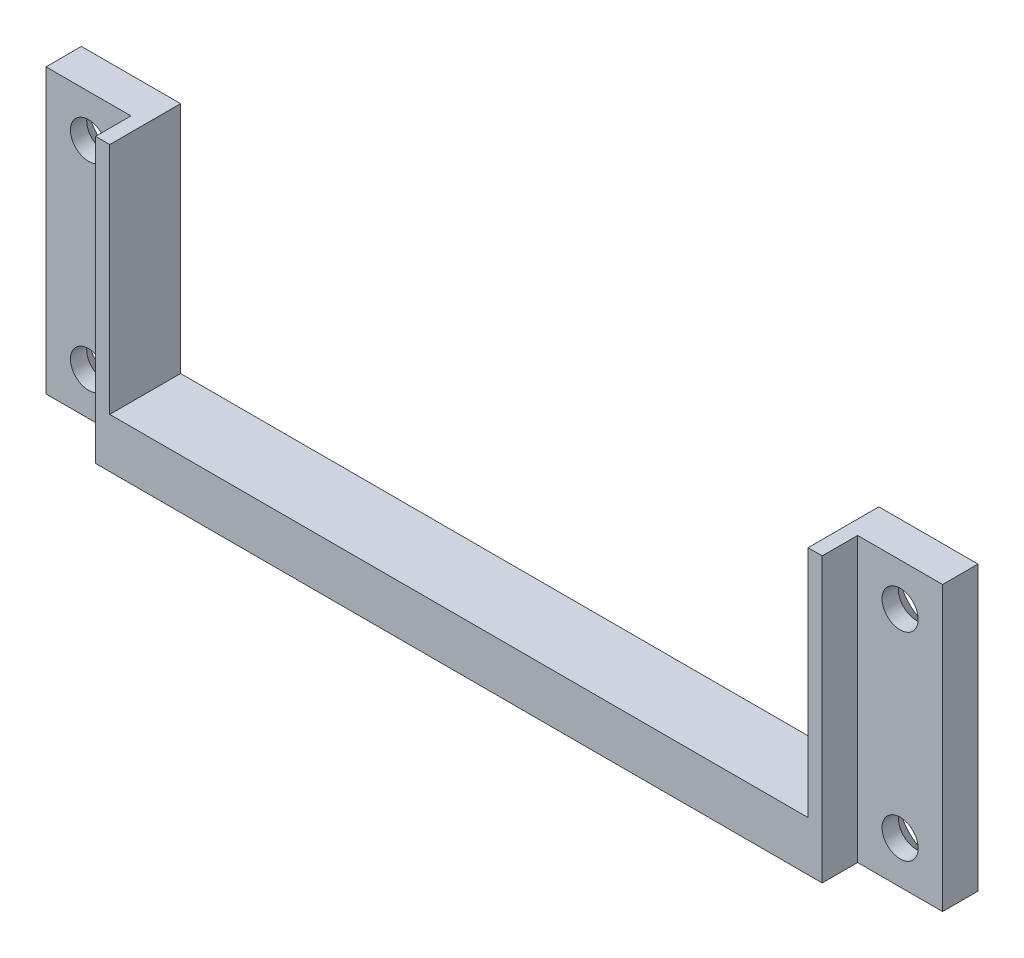
SolidWorks part; units mm, degrees
ref_plane "Plan de face" through (0, 0, 0) normal (0, 0, 1) x (1, 0, 0)
ref_plane "Plan de dessus" through (0, 0, 0) normal (0, 1, 0) x (1, 0, 0)
ref_plane "Plan de droite" through (0, 0, 0) normal (1, 0, 0) x (0, 0, -1)
sketch "Esquisse1" plane through (0, 0, 0) normal (0, 0, 1) x (1, 0, 0)
  line L1 (-17.4678, 19.1867) -> (85.1322, 19.1867)
  line L2 (-17.4678, 19.1867) -> (-17.4678, -15.8133)
  line L3 (-17.4678, -15.8133) -> (85.1322, -15.8133)
  line L4 (85.1322, 19.1867) -> (85.1322, -15.8133)
  dimension "D1" = 35
  dimension "D2" = 102.6
extrude "Boss.-Extru.1" add sketch "Esquisse1" along normal blind 10 and the other way blind 0.0001
sketch "Esquisse4" plane through (0, 19.1867, 0) normal (0, 1, 0) x (1, 0, 0)
  line L1 (-15.4678, -51.5999) -> (83.1322, -51.5999)
  line L2 (-15.4678, -51.5999) -> (-15.4678, 0.0001)
  line L3 (-15.4678, 0.0001) -> (83.1322, 0.0001)
  line L4 (83.1322, -51.5999) -> (83.1322, 0.0001)
  line L5 (-17.4678, -10) -> (-17.4678, 0.0001) construction
  line L6 (85.1322, -10) -> (85.1322, 0.0001) construction
  line L7 (85.1322, 0.0001) -> (-17.4678, 0.0001) construction
  dimension "D1" = 51.6
  dimension "D2" = 98.6
  dimension "D3" = 0
  dimension "D4" = 2
  dimension "D5" = 2
extrude "Enlèv. mat.-Extru.2" cut sketch "Esquisse4" against normal blind 33
sketch "Esquisse19" plane through (0, -15.8133, 0) normal (0, -1, 0) x (1, 0, 0)
  line L1 (85.1322, -0.0001) -> (-17.4678, -0.0001)
  line L2 (85.1322, -0.0001) -> (85.1322, 10)
  line L3 (85.1322, 10) -> (-17.4678, 10)
  line L4 (-17.4678, -0.0001) -> (-17.4678, 10)
extrude "Boss.-Extru.4" add sketch "Esquisse19" along normal blind 5
sketch "Esquisse21" plane through (-17.4678, 0, 0) normal (-1, 0, 0) x (0, 0, 1)
  line L0 (10, -20.8133) -> (-0.0001, -20.8133) construction
  line L1 (-0.0001, 19.1867) -> (4.9999, 19.1867)
  line L2 (-0.0001, 19.1867) -> (-0.0001, -20.8133)
  line L3 (-0.0001, -20.8133) -> (4.9999, -20.8133)
  line L4 (4.9999, 19.1867) -> (4.9999, -20.8133)
  dimension "D1" = 5
extrude "Boss.-Extru.5" add sketch "Esquisse21" along normal blind 12
sketch "Esquisse22" plane through (85.1322, 0, 0) normal (1, 0, 0) x (0, 0, -1)
  line L0 (0.0001, -20.8133) -> (-10, -20.8133) construction
  line L1 (0.0001, 19.1867) -> (-4.9999, 19.1867)
  line L2 (0.0001, 19.1867) -> (0.0001, -20.8133)
  line L3 (0.0001, -20.8133) -> (-4.9999, -20.8133)
  line L4 (-4.9999, 19.1867) -> (-4.9999, -20.8133)
  dimension "D1" = 5
extrude "Boss.-Extru.6" add sketch "Esquisse22" along normal blind 12
sketch "Esquisse23" plane through (0, 0, -0.0001) normal (0, 0, -1) x (-1, 0, 0)
  line L0 (-97.1322, -20.8133) -> (-97.1322, 19.1867) construction
  line L2 (-97.1322, 19.1867) -> (-83.1322, 19.1867) construction
  line L3 (29.4678, -20.8133) -> (-97.1322, -20.8133) construction
  line L4 (29.4678, 19.1867) -> (29.4678, -20.8133) construction
  line L5 (15.4678, 19.1867) -> (29.4678, 19.1867) construction
  circle A0 centre (-91.1322, 13.1867) radius 5.25
  circle A1 centre (-91.1322, -14.8133) radius 5.25
  circle A2 centre (23.4678, 13.1867) radius 5.25
  circle A3 centre (23.4678, -14.8133) radius 5.25
  dimension "D3" = 10.5
  dimension "D10" = 10.5
  dimension "D11" = 10.5
  dimension "D12" = 10.5
  dimension "D1" = 6
  dimension "D2" = 6
  dimension "D4" = 6
  dimension "D5" = 6
  dimension "D6" = 6
  dimension "D7" = 6
  dimension "D8" = 6
  dimension "D9" = 6
hole_wizard "Fraisage pour vis à tête fraisée bombée #51" positions "Esquisse3D1" profile "Esquisse24" countersink size "#5" standard "Ansi Inch" end condition through all
sketch3d "Esquisse3D1"
  point P0 (91.1322, 13.1867, -0.0001)
  point P3 (91.1322, -14.8133, -0.0001)
  point P6 (-23.4678, 13.1867, -0.0001)
  point P9 (-23.4678, -14.8133, -0.0001)
sketch "Esquisse24" plane through (91.1322, 13.1867, -0.0001) normal (1, 0, 0) x (0, 1, 0)
  line L0 (0, 0) -> (0, 10.0001)
  line L1 (0, 10.0001) -> (2.55, 10.0001)
  line L2 (2.55, 10.0001) -> (2.55, 2.7)
  line L3 (2.55, 2.7) -> (5.25, 0)
  line L5 (5.25, 0) -> (0, 0)
  line L6 (-2.55, 2.7) -> (-5.25, 0) construction
  line L11 (0, -6.35) -> (0, 107.95) construction
  dimension "Diamètre du perçage jusqu'au prochain" = 5.1
  dimension "Profondeur du perçage jusqu'au prochain" = 10.0001
  dimension "Diamètre du fraisage entrant" = 10.5
  dimension "Angle du fraisage entrant" = 90
sketch "Sketch1" plane through (0, -20.8133, 0) normal (0, -1, 0) x (-1, 0, 0)
  line L0 (29.4678, 0.0001) -> (-33.8322, 0.0001)
  line L1 (29.4678, 0.0001) -> (-97.1322, 0.0001) construction
  line L2 (-33.8322, 0.0001) -> (-33.8322, -10)
  line L3 (-85.1322, -10) -> (17.4678, -10) construction
sketch "Sketch3" plane through (0, -20.8133, 0) normal (0, -1, 0) x (-1, 0, 0)
  line L0 (29.4678, -4.9999) -> (-33.8322, -4.9999)
